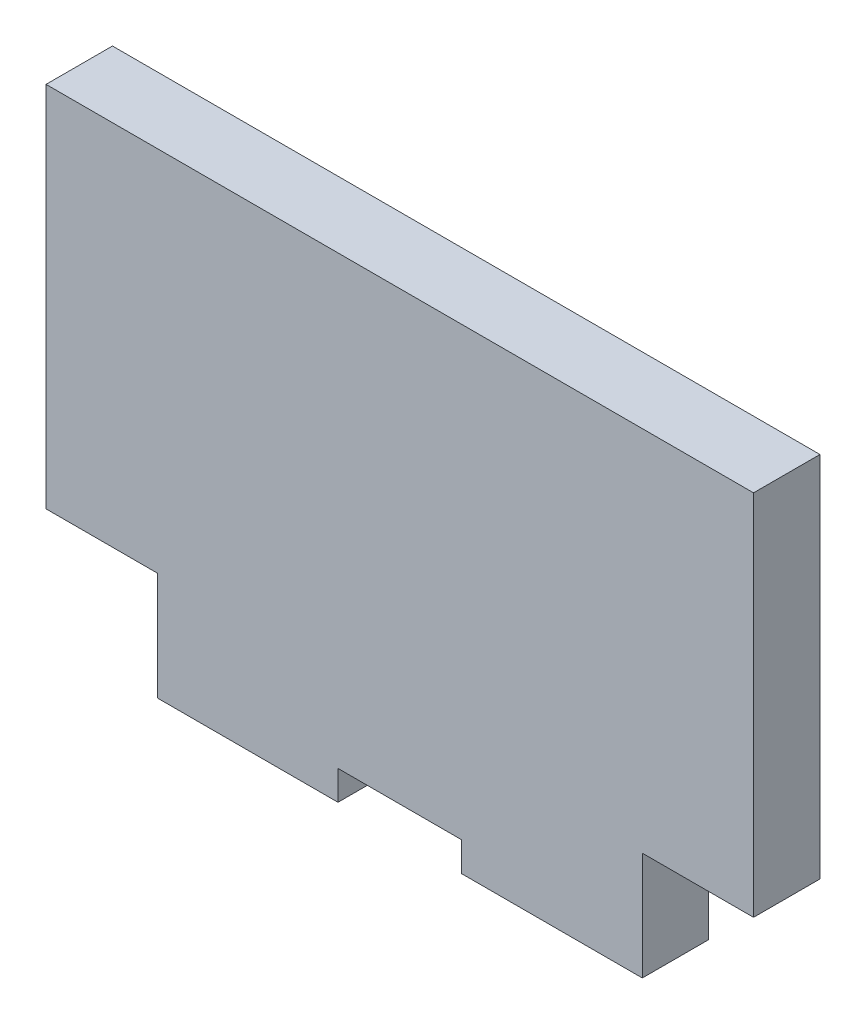
SolidWorks part; units mm, degrees
ref_plane "Front Plane" through (0, 0, 0) normal (0, 0, 1) x (1, 0, 0)
ref_plane "Top Plane" through (0, 0, 0) normal (0, 1, 0) x (1, 0, 0)
ref_plane "Right Plane" through (0, 0, 0) normal (1, 0, 0) x (0, 0, -1)
sketch "Sketch2" plane through (0, 0, 0) normal (0, 0, 1) x (1, 0, 0)
  line L1 (4, -15.4) -> (-15.7, -15.4)
  line L2 (-15.7, -15.4) -> (-15.7, -8.4)
  line L3 (-15.7, -8.4) -> (-22.9, -8.4)
  line L4 (-22.9, -8.4) -> (-22.9, 15.4)
  line L5 (-22.9, 15.4) -> (22.9, 15.4)
  line L6 (22.9, 15.4) -> (22.9, -8.4)
  line L7 (22.9, -8.4) -> (15.7, -8.4)
  line L8 (15.7, -8.4) -> (15.7, -15.4)
  line L9 (15.7, -15.4) -> (4, -15.4)
  line L17 (4, -15.5) -> (4, -16.5)
  line L18 (4, -16.5) -> (24, -16.5)
  line L19 (24, -16.5) -> (24, 16.5)
  line L20 (24, 16.5) -> (-24, 16.5)
  line L21 (-24, 16.5) -> (-24, -16.5)
  line L22 (-24, -16.5) -> (-4, -16.5)
  line L23 (-4, -16.5) -> (-4, -15.5)
  line L24 (-4, -15.5) -> (-15.8, -15.5)
  line L25 (-15.8, -15.5) -> (-15.8, -8.5)
  line L26 (-15.8, -8.5) -> (-23, -8.5)
  line L27 (-23, -8.5) -> (-23, 15.5)
  line L28 (-23, 15.5) -> (23, 15.5)
  line L29 (23, 15.5) -> (23, -8.5)
  line L30 (23, -8.5) -> (15.8, -8.5)
  line L31 (15.8, -8.5) -> (15.8, -15.5)
  line L32 (15.8, -15.5) -> (4, -15.5)
  line L40 (4, -15.5) -> (-15.8, -15.5) construction
  line L41 (-15.8, -15.5) -> (-15.8, -8.5) construction
  line L42 (-15.8, -8.5) -> (-23, -8.5) construction
  line L43 (-23, -8.5) -> (-23, 15.5) construction
  line L44 (-23, 15.5) -> (23, 15.5) construction
  line L45 (23, 15.5) -> (23, -8.5) construction
  line L46 (23, -8.5) -> (15.8, -8.5) construction
  line L47 (15.8, -8.5) -> (15.8, -15.5) construction
  line L48 (15.8, -15.5) -> (4, -15.5) construction
  point P0 (4.5903, -15.5)
  dimension "D1" = 0
  dimension "D2" = 0.1
extrude "Boss-Extrude1" add sketch "Sketch2" against normal blind 4.3
sketch "Sketch3" plane through (0, 0, 0) normal (0, 0, 1) x (1, 0, 0)
  line L1 (-4, -15.5) -> (4, -15.5)
  line L2 (-4, -15.5) -> (-4, -13.5)
  line L3 (-4, -13.5) -> (4, -13.5)
  line L4 (4, -15.5) -> (4, -13.5)
  point P4 (4, -15.5)
  dimension "D1" = 2
extrude "Cut-Extrude1" cut sketch "Sketch3" against normal blind 4.3
sketch "Sketch4" plane through (0, 0, -4.3) normal (0, 0, -1) x (-1, 0, 0)
  line L0 (0, 0) -> (0, -21.4597) construction
  line L1 (-4, -13.5) -> (4, -13.5) construction
  line L2 (-5.5, -1.5) -> (5.5, -1.5)
  line L3 (-5.5, -1.5) -> (-5.5, -13.5)
  line L4 (-5.5, -13.5) -> (5.5, -13.5)
  line L5 (5.5, -1.5) -> (5.5, -13.5)
  line L6 (-5.5, -1.5) -> (5.5, -13.5) construction
  line L7 (-5.5, -13.5) -> (5.5, -1.5) construction
  line L8 (15.8, -15.5) -> (-15.8, -15.5) construction
  point P3 (0, -7.5)
  point P10 (5.8756, -13.5)
  dimension "D1" = 11
  dimension "D2" = 14
extrude "Cut-Extrude2" cut sketch "Sketch4" against normal blind 3.3
